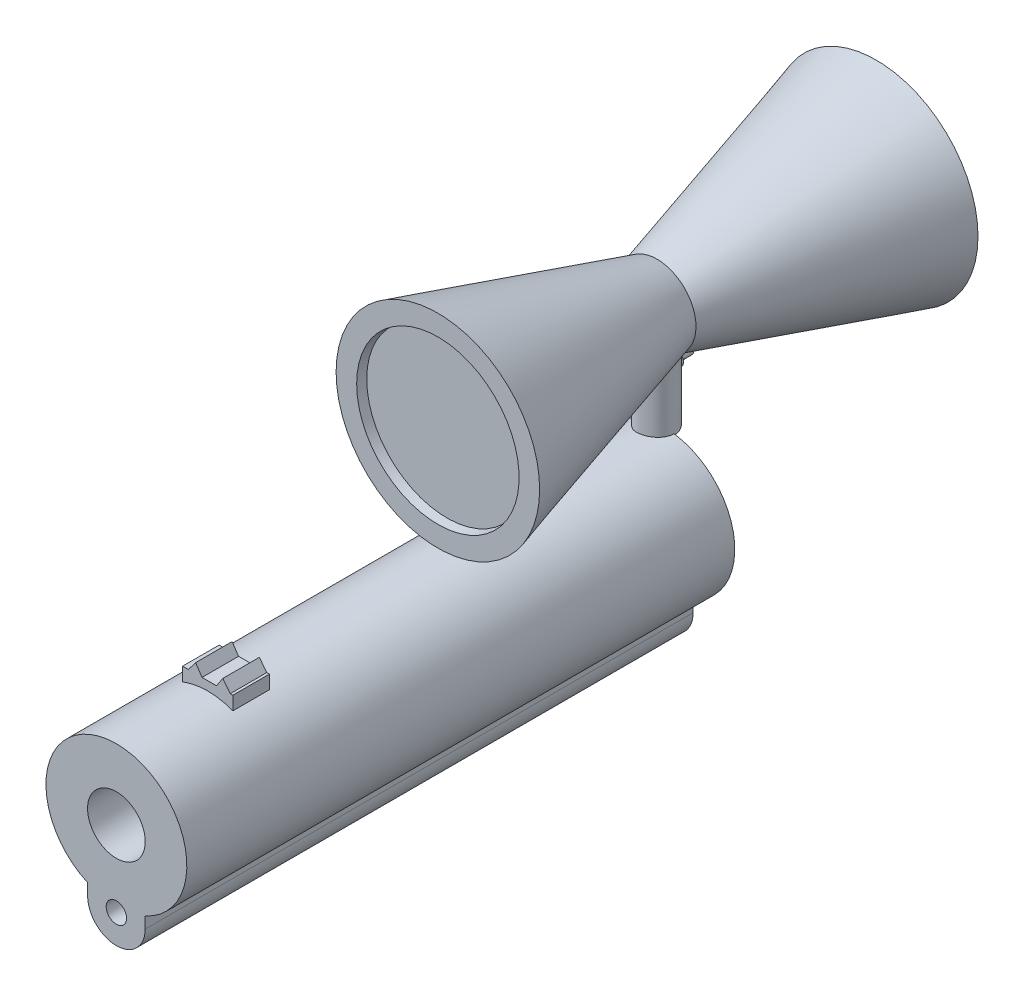
SolidWorks part; units mm, degrees
ref_plane "Front Plane" through (0, 0, 0) normal (0, 0, 1) x (1, 0, 0)
ref_plane "Top Plane" through (0, 0, 0) normal (0, 1, 0) x (1, 0, 0)
ref_plane "Right Plane" through (0, 0, 0) normal (1, 0, 0) x (0, 0, -1)
sketch "Sketch1" plane through (0, 0, 0) normal (0, 0, 1) x (1, 0, 0)
  line L0 (-6.3002, -14.0827) -> (-6.3002, -16.5855)
  line L1 (6.3002, -14.0827) -> (6.3002, -16.5855)
  circle A0 centre (0, 0) radius 6.3166
  circle A1 centre (0, 0) radius 15.4278
  arc A2 (-6.3002, -16.5855) -> (6.3002, -16.5855) centre (0, -16.5855) ccw
extrude "Boss-Extrude1" add sketch "Sketch1" against normal blind 120 contours L0 A2 L1 A1 | A1 A0
sketch "Sketch2" plane through (0, 0, 0) normal (0, 0, 1) x (1, 0, 0)
  circle A0 centre (0, -16.5855) radius 2.2329
extrude "Cut-Extrude1" cut sketch "Sketch2" against normal through all
ref_plane "Plane1" through (0, 0, -20) normal (0, 0, 1) x (1, 0, 0)
sketch "Sketch3" plane through (0, 0, -20) normal (0, 0, 1) x (1, 0, 0)
  line L0 (-5.5074, 14.4113) -> (-5.5074, 17.3817)
  line L1 (-5.5074, 17.3817) -> (-4.2414, 17.3817)
  line L2 (-4.2414, 17.3817) -> (-2.6598, 19.4709)
  line L3 (-2.6598, 19.4709) -> (-1.2414, 17.3817)
  line L4 (-1.2414, 17.3817) -> (1.925, 17.3817)
  line L5 (1.925, 17.3817) -> (3.3112, 19.4709)
  line L6 (3.3112, 19.4709) -> (4.925, 17.3817)
  line L7 (4.925, 17.3817) -> (5.5074, 17.3817)
  line L8 (5.5074, 17.3817) -> (5.5074, 14.4113)
  line L9 (-5.5074, 14.4113) -> (5.5074, 14.4113)
  arc A0 (6.3002, -14.0827) -> (-6.3002, -14.0827) centre (0, 0) ccw construction
  dimension "D1" = 3
  dimension "D2" = 3
extrude "Boss-Extrude2" add sketch "Sketch3" against normal blind 8
ref_plane "Plane2" through (0, 0, -120) normal (0, 0, -1) x (-1, 0, 0)
sketch "Sketch4" plane through (0, 0, -120) normal (0, 0, -1) x (-1, 0, 0)
  circle A0 centre (1.596, 38.0077) radius 8.5255
  point P2 (0, 37.6513)
  point P3 (1.5506, 37.1461)
  point P4 (0, 0)
  point P5 (0, 23.9533)
  point P6 (1.596, 38.0077)
extrude "Boss-Extrude3" add sketch "Sketch4" along normal blind 48 draft 16 separate body draft outward yes
sketch "Sketch6" plane through (0, 0, -168) normal (0, 0, -1) x (-1, 0, 0)
  circle A0 centre (1.596, 38.0077) radius 17.7885
extrude "Cut-Extrude2" cut sketch "Sketch6" against normal blind 2 draft 6
mirror "Mirror2" about plane through (-1.596, 38.0077, -120) normal (0, 0, -1) of bodies 105
ref_plane "Plane3" through (0, 15, 0) normal (0, 1, 0) x (1, 0, 0)
sketch "Sketch9" plane through (0, 15, 0) normal (0, 1, 0) x (1, 0, 0)
  line L0 (16.9705, 120) -> (-16.9705, 120) construction
  circle A0 centre (-1.7234, 120) radius 3.8512
extrude "Boss-Extrude4" add sketch "Sketch9" along normal blind 17
sketch "Sketch10" plane through (0, 0, -120) normal (0, 0, -1) x (-1, 0, 0)
  circle A0 centre (5.5399, 21.9288) radius 1.7429
extrude "Boss-Extrude5" add sketch "Sketch10" along normal blind 8
sketch "Sketch11" plane through (0, 0, -128) normal (0, 0, -1) x (-1, 0, 0)
  circle A0 centre (5.5399, 21.9288) radius 0.9231
extrude "Boss-Extrude6" add sketch "Sketch11" along normal blind 3
